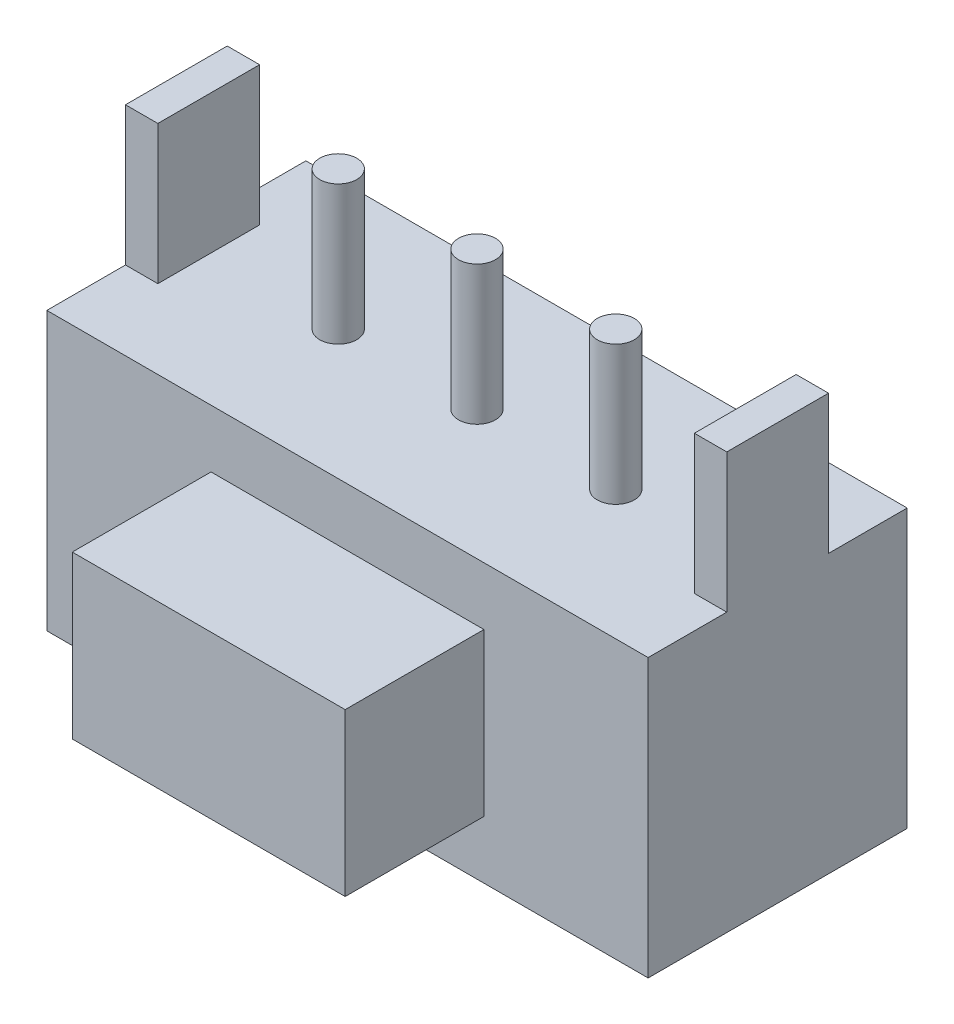
SolidWorks part; units mm, degrees
ref_plane "Front Plane" through (0, 0, 0) normal (0, 0, 1) x (1, 0, 0)
ref_plane "Top Plane" through (0, 0, 0) normal (0, 1, 0) x (1, 0, 0)
ref_plane "Right Plane" through (0, 0, 0) normal (1, 0, 0) x (0, 0, -1)
sketch "Sketch1" plane through (0, 0, 0) normal (0, 1, 0) x (1, 0, 0)
  line L1 (-6.5, 2.8) -> (6.5, 2.8)
  line L2 (-6.5, 2.8) -> (-6.5, -2.8)
  line L3 (-6.5, -2.8) -> (6.5, -2.8)
  line L4 (6.5, 2.8) -> (6.5, -2.8)
  line L5 (-6.5, 2.8) -> (6.5, -2.8) construction
  line L6 (-6.5, -2.8) -> (6.5, 2.8) construction
  point P0 (0, 0)
  dimension "D1" = 5.6
  dimension "D2" = 13
extrude "Boss-Extrude1" add sketch "Sketch1" along normal blind 6
sketch "Sketch2" plane through (0, 6, 0) normal (0, 1, 0) x (1, 0, 0)
  line L0 (-6.5, 2.8) -> (-6.5, -2.8) construction
  line L1 (-6.5, -1.1) -> (-5.8, -1.1)
  line L2 (-6.5, -1.1) -> (-6.5, 1.1)
  line L3 (-6.5, 1.1) -> (-5.8, 1.1)
  line L4 (-5.8, -1.1) -> (-5.8, 1.1)
  line L5 (6.5, 0) -> (-6.5, 0) construction
  line L6 (6.5, -2.8) -> (6.5, 2.8) construction
  line L7 (0, -2.8) -> (0, 2.8) construction
  line L8 (-6.5, -2.8) -> (6.5, -2.8) construction
  line L9 (6.5, 2.8) -> (-6.5, 2.8) construction
  line L10 (6.5, -1.1) -> (5.8, -1.1)
  line L11 (6.5, -1.1) -> (6.5, 1.1)
  line L12 (6.5, 1.1) -> (5.8, 1.1)
  line L13 (5.8, -1.1) -> (5.8, 1.1)
  circle A0 centre (-3, 0) radius 0.4
  circle A1 centre (0, 0) radius 0.4
  circle A2 centre (3, 0) radius 0.4
  dimension "D3" = 0.8
  dimension "D6" = 2.8
  dimension "D7" = 3
  dimension "D1" = 2.2
  dimension "D2" = 0.7
  dimension "D4" = 3
  dimension "D5" = 3
extrude "Boss-Extrude2" add sketch "Sketch2" along normal blind 3
sketch "Sketch3" plane through (0, 0, 2.8) normal (0, 0, 1) x (1, 0, 0)
  line L0 (0, 0) -> (0, 6) construction
  line L1 (-6.5, 6) -> (6.5, 6) construction
  line L2 (-6.5, 3) -> (6.5, 3) construction
  line L3 (-6.5, 6) -> (-6.5, 0) construction
  line L4 (6.5, 6) -> (6.5, 0) construction
  line L6 (-2.95, 4.75) -> (2.95, 4.75)
  line L7 (-2.95, 4.75) -> (-2.95, 1.25)
  line L8 (-2.95, 1.25) -> (2.95, 1.25)
  line L9 (2.95, 4.75) -> (2.95, 1.25)
  line L10 (-2.95, 4.75) -> (2.95, 1.25) construction
  line L11 (-2.95, 1.25) -> (2.95, 4.75) construction
  point P11 (0, 3)
  dimension "D1" = 3.5
  dimension "D2" = 3.55
extrude "Boss-Extrude3" add sketch "Sketch3" along normal blind 3
